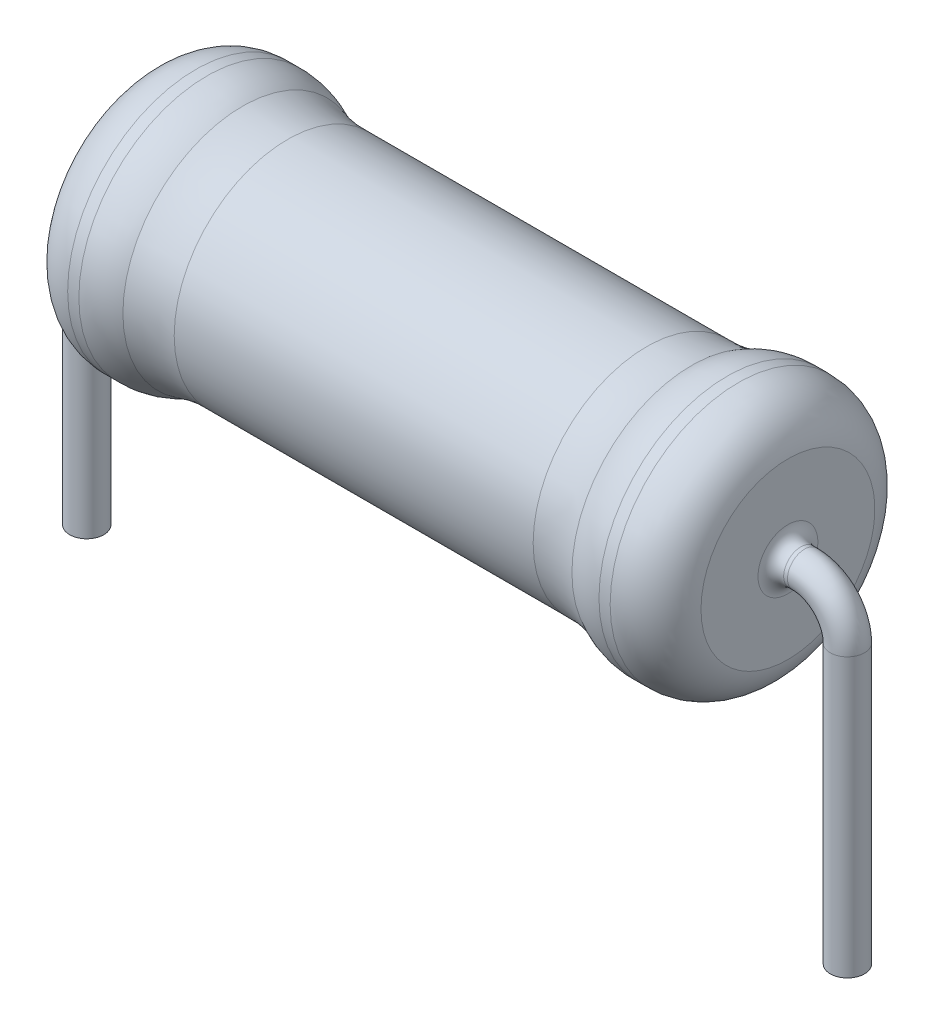
SolidWorks part; units mm, degrees
ref_plane "Front Plane" through (0, 0, 0) normal (0, 0, 1) x (1, 0, 0)
ref_plane "Top Plane" through (0, 0, 0) normal (0, 1, 0) x (1, 0, 0)
ref_plane "Right Plane" through (0, 0, 0) normal (1, 0, 0) x (0, 0, -1)
sketch "Sketch1" plane through (0, 0, 0) normal (0, 1, 0) x (1, 0, 0)
  line L0 (8.89, 0) -> (-8.89, 0) construction
  line L1 (0, 0) -> (0, 12.1522) construction
  circle A1 centre (8.89, 0) radius 0.4
  dimension "D1" = 8.89
extrude "Boss-Extrude1" add sketch "Sketch1" along normal blind 5.3
sketch "Sketch2" plane through (0, 0, 0) normal (0, 0, 1) x (1, 0, 0)
  line L0 (-7.5, 7.5) -> (7.5, 7.5)
  line L1 (0, 0) -> (0, 7.5) construction
  line L2 (-7.5, 7.5) -> (-7.5, 9.5323)
  line L3 (7.5, 9.5323) -> (7.5, 7.5)
  line L4 (6.0788, 10.4959) -> (6.3404, 10.4959)
  line L5 (-4.1953, 10.1508) -> (4.1953, 10.1508)
  line L6 (-6.0788, 10.4959) -> (-6.3404, 10.4959)
  arc A0 (-6.0788, 10.4959) -> (-5.2478, 10.2972) centre (-6.0115, 8.9406) cw
  arc A1 (-7.5, 9.5323) -> (-6.3404, 10.4959) centre (-6.3366, 9.3119) cw
  arc A2 (5.2478, 10.2972) -> (4.1953, 10.1508) centre (4.3263, 13.0654) cw
  arc A3 (-5.2478, 10.2972) -> (-4.1953, 10.1508) centre (-4.3263, 13.0654) ccw
  arc A4 (7.5, 9.5323) -> (6.3404, 10.4959) centre (6.3366, 9.3119) ccw
  arc A5 (6.0788, 10.4959) -> (5.2478, 10.2972) centre (6.0115, 8.9406) ccw
  point P6 (0, 9.375)
  point P8 (-4.75, 9.375)
  point P10 (0, 10.5)
  point P11 (-4.572, 10.5)
  point P14 (0.428, 7.5)
  point P17 (0.428, 11)
revolve "Revolve1" add sketch "Sketch2" angle 360 about L0
sketch "Sketch3" plane through (0, 0, 0) normal (0, 0, 1) x (1, 0, 0)
  line L0 (3.5, 7.5) -> (-3.5, 7.5) construction
  line L1 (8.49, 0) -> (9.29, 0) construction
  line L3 (0, 7.5) -> (0, 4.5) construction
  line L5 (3.5, 7.5) -> (7.89, 7.5)
  line L6 (8.89, 6.5) -> (8.89, 5.3)
  line L7 (9.29, 5.3) -> (8.49, 5.3) construction
  arc A0 (8.89, 6.5) -> (7.89, 7.5) centre (7.89, 6.5) ccw
  dimension "D1" = 1.2
  dimension "D3" = 1
  dimension "D2" = 7.5
  dimension "D4" = 8.89
sketch "Sketch4" plane through (0, 5.3, 0) normal (0, 1, 0) x (1, 0, 0)
  circle A2 centre (8.89, 0) radius 0.4
  dimension "D1" = 0.8
sweep "Sweep1" add profiles "Sketch4" path "Sketch3"
mirror "Mirror1" about plane through (0, 0, 0) normal (1, 0, 0) of "Sweep1", "Boss-Extrude1"
fillet "Fillet1" radius 0.3 2 edges at (7.5, 7.5, -0.4) (-7.5, 7.5, 0.4)
